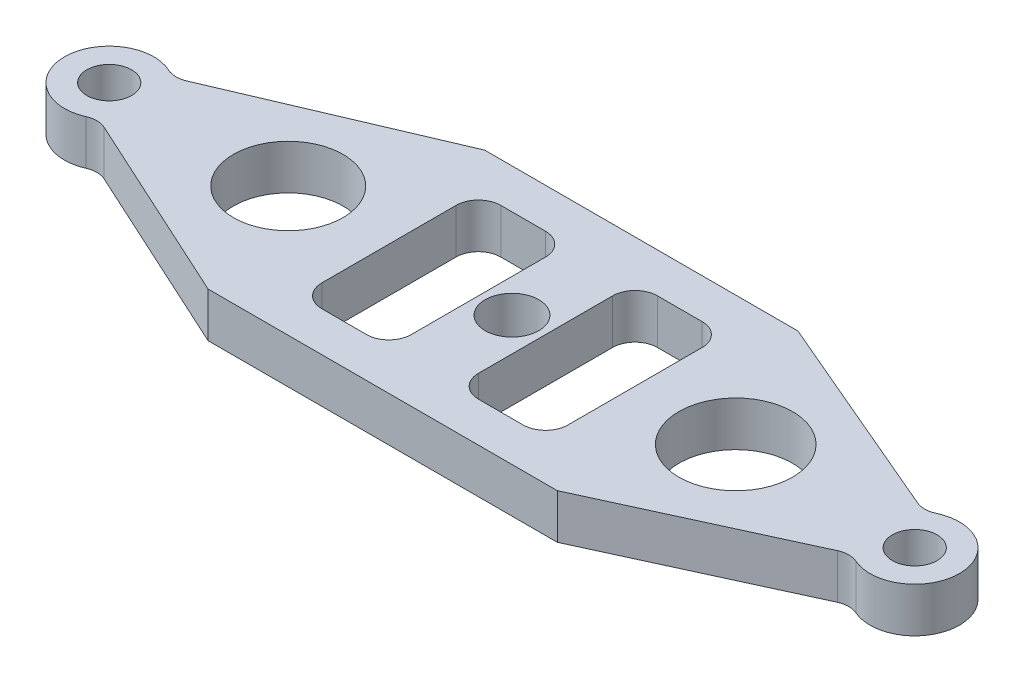
SolidWorks part; units mm, degrees
material "Aleación 1060"
ref_plane "Alzado" through (0, 0, 0) normal (0, 0, 1) x (1, 0, 0)
ref_plane "Planta" through (0, 0, 0) normal (0, 1, 0) x (1, 0, 0)
ref_plane "Vista lateral" through (0, 0, 0) normal (1, 0, 0) x (0, 0, -1)
sketch "Croquis1" plane through (0, 0, 0) normal (0, 1, 0) x (1, 0, 0)
  line L0 (-50, 0) -> (50, 0) construction
  line L1 (0, -28.8919) -> (0, 28.8919) construction
  line L2 (50, 0) -> (90, 0) construction
  line L3 (-50, 0) -> (-90, 0) construction
  line L4 (-35, 28.8919) -> (35, 28.8919)
  line L5 (-39.0176, -28.8919) -> (39.0176, -28.8919)
  line L6 (35, 28.8919) -> (81.6773, 8.9851)
  line L7 (-35, 28.8919) -> (-81.6773, 8.9851)
  line L8 (-39.0176, -28.8919) -> (-81.9232, -9.2068)
  line L9 (39.0176, -28.8919) -> (81.9232, -9.2068)
  line L10 (-35, 28.8919) -> (0, -28.8919) construction
  line L11 (35, 28.8919) -> (0, -28.8919) construction
  line L12 (-22.5, 20) -> (-12.5, 20)
  line L13 (-27.5, 15) -> (-27.5, -15)
  line L14 (-22.5, -20) -> (-12.5, -20)
  line L15 (-7.5, 15) -> (-7.5, -15)
  line L16 (-27.5, 20) -> (-7.5, -20) construction
  line L17 (-27.5, -20) -> (-7.5, 20) construction
  line L18 (12.5, 20) -> (22.5, 20)
  line L19 (7.5, 15) -> (7.5, -15)
  line L20 (12.5, -20) -> (22.5, -20)
  line L21 (27.5, 15) -> (27.5, -15)
  line L22 (7.5, 20) -> (27.5, -20) construction
  line L23 (7.5, -20) -> (27.5, 20) construction
  circle A0 centre (50, 0) radius 12.7
  circle A1 centre (-50, 0) radius 12.25
  circle A2 centre (-90, 0) radius 5
  circle A3 centre (90, 0) radius 5
  circle A4 centre (0, 0) radius 6
  arc A5 (7.5, -15) -> (12.5, -20) centre (12.5, -15) ccw
  arc A6 (22.5, -20) -> (27.5, -15) centre (22.5, -15) ccw
  arc A7 (27.5, 15) -> (22.5, 20) centre (22.5, 15) ccw
  arc A8 (7.5, 15) -> (12.5, 20) centre (12.5, 15) cw
  arc A9 (-27.5, -15) -> (-22.5, -20) centre (-22.5, -15) ccw
  arc A10 (-12.5, -20) -> (-7.5, -15) centre (-12.5, -15) ccw
  arc A11 (-7.5, 15) -> (-12.5, 20) centre (-12.5, 15) ccw
  arc A12 (-27.5, 15) -> (-22.5, 20) centre (-22.5, 15) cw
  arc A13 (-85.7592, 9.0562) -> (-86.0055, -9.1675) centre (-90, 0) ccw
  arc A14 (86.0055, -9.1675) -> (85.7592, 9.0562) centre (90, 0) ccw
  arc A15 (81.9232, -9.2068) -> (86.0055, -9.1675) centre (84.0082, -13.7513) cw
  arc A16 (85.7592, 9.0562) -> (81.6773, 8.9851) centre (83.6388, 13.5844) cw
  arc A17 (-81.9232, -9.2068) -> (-86.0055, -9.1675) centre (-84.0082, -13.7513) ccw
  arc A18 (-81.6773, 8.9851) -> (-85.7592, 9.0562) centre (-83.6388, 13.5844) cw
  point P4 (0, 0)
  point P7 (0, 0)
  point P16 (0, 28.8919)
  point P19 (0, -28.8919)
  point P21 (-17.5, 0)
  point P27 (17.5, 0)
  dimension "D1" = 24.5
  dimension "D2" = 25.4
  dimension "D5" = 10
  dimension "D6" = 10
  dimension "D7" = 5
  dimension "D8" = 5
  dimension "D13" = 10
  dimension "D14" = 10
  dimension "D3" = 40
  dimension "D4" = 70
  dimension "D9" = 50
  dimension "D10" = 50
  dimension "D11" = 40
  dimension "D12" = 40
  dimension "D15" = 20
  dimension "D16" = 40
  dimension "D17" = 40
  dimension "D18" = 20
extrude "Saliente-Extruir1" add sketch "Croquis1" along normal blind 10
